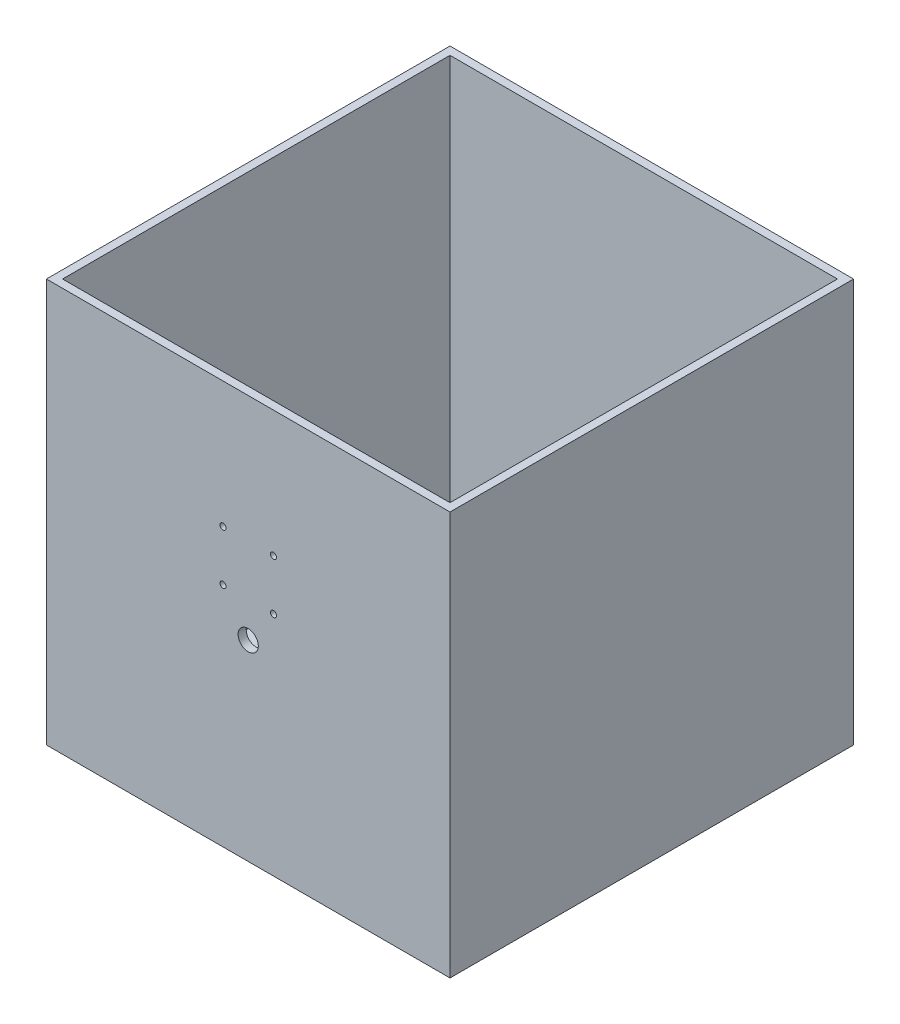
SolidWorks part; units mm, degrees
material "Perspex (TM) GS Acrylic Cast Sheet"
ref_plane "Front Plane" through (0, 0, 0) normal (0, 0, 1) x (1, 0, 0)
ref_plane "Top Plane" through (0, 0, 0) normal (0, 1, 0) x (1, 0, 0)
ref_plane "Right Plane" through (0, 0, 0) normal (1, 0, 0) x (0, 0, -1)
sketch "Sketch1" plane through (0, 0, 0) normal (0, 1, 0) x (1, 0, 0)
  line L1 (-100, -100) -> (100, -100)
  line L2 (-100, -100) -> (-100, 100)
  line L3 (-100, 100) -> (100, 100)
  line L4 (100, -100) -> (100, 100)
  line L5 (-100, -100) -> (100, 100) construction
  line L6 (-100, 100) -> (100, -100) construction
  point P0 (0, 0)
  dimension "D1" = 200
  dimension "D2" = 200
extrude "Boss-Extrude1" add sketch "Sketch1" along normal blind 200
shell "Shell1" thickness 4
sketch "Sketch2" plane through (0, 0, 100) normal (0, 0, 1) x (1, 0, 0)
  line L0 (0, -110) -> (0, 110) construction
  line L1 (-12.5, 112.5) -> (12.5, 112.5) construction
  line L2 (-12.5, 112.5) -> (-12.5, 137.5) construction
  line L3 (-12.5, 137.5) -> (12.5, 137.5) construction
  line L4 (12.5, 112.5) -> (12.5, 137.5) construction
  line L5 (-12.5, 112.5) -> (12.5, 137.5) construction
  line L6 (-12.5, 137.5) -> (12.5, 112.5) construction
  line L7 (-100, 200) -> (100, 200) construction
  circle A0 centre (-12.5, 137.5) radius 1.5
  circle A1 centre (12.5, 137.5) radius 1.5
  circle A2 centre (12.5, 112.5) radius 1.5
  circle A3 centre (-12.5, 112.5) radius 1.5
  circle A4 centre (0, 95) radius 5
  point P0 (0, 125)
  dimension "D4" = 3
  dimension "D5" = 10
  dimension "D1" = 25
  dimension "D2" = 25
  dimension "D3" = 75
  dimension "D6" = 30
extrude "Cut-Extrude1" cut sketch "Sketch2" against normal up to next
